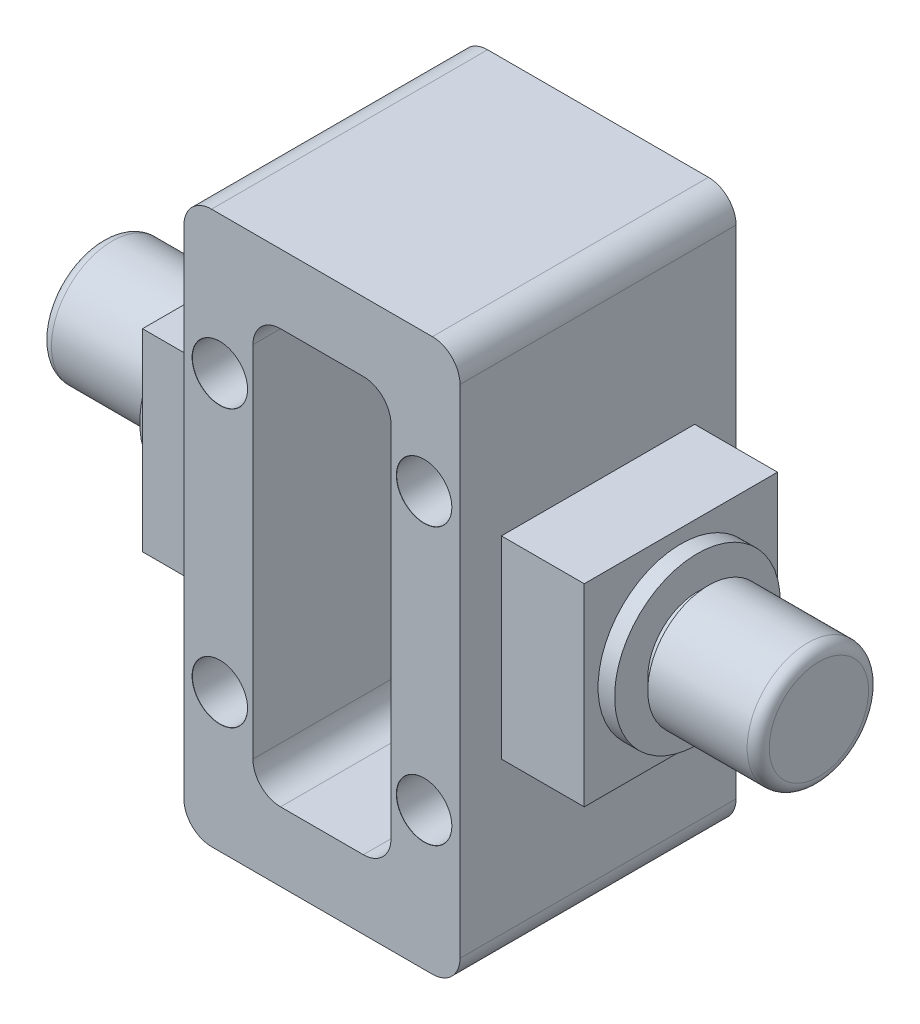
SolidWorks part; units mm, degrees
ref_plane "Front Plane" through (0, 0, 0) normal (0, 0, 1) x (1, 0, 0)
ref_plane "Top Plane" through (0, 0, 0) normal (0, 1, 0) x (1, 0, 0)
ref_plane "Right Plane" through (0, 0, 0) normal (1, 0, 0) x (0, 0, -1)
sketch "Sketch1" plane through (0, 0, 0) normal (1, 0, 0) x (0, 0, -1)
  line L1 (-25, 50) -> (25, 50)
  line L2 (-25, 50) -> (-25, -50)
  line L3 (-25, -50) -> (25, -50)
  line L4 (25, 50) -> (25, -50)
  line L5 (-25, 50) -> (25, -50) construction
  line L6 (-25, -50) -> (25, 50) construction
  point P0 (0, 0)
  dimension "D1" = 50
  dimension "D2" = 100
extrude "Boss-Extrude1" add sketch "Sketch1" along normal mid plane 50
fillet "Fillet1" radius 5 4 edges at (-25, 50, 0) (-25, -50, 0) (25, -50, 0) (25, 50, 0)
sketch "Sketch2" plane through (0, 0, 25) normal (0, 0, 1) x (1, 0, 0)
  line L8 (12.5, 37.5) -> (-12.5, 37.5)
  line L9 (-12.5, 37.5) -> (-12.5, -37.5)
  line L10 (-12.5, -37.5) -> (12.5, -37.5)
  line L11 (12.5, -37.5) -> (12.5, 37.5)
  line L12 (12.5, 37.5) -> (-12.5, 37.5)
  line L13 (-12.5, 37.5) -> (-12.5, -37.5)
  line L14 (-12.5, -37.5) -> (12.5, -37.5)
  line L15 (12.5, -37.5) -> (12.5, 37.5)
  dimension "D1" = 12.5
extrude "Cut-Extrude1" cut sketch "Sketch2" against normal blind 50
fillet "Fillet2" radius 5 4 edges at (12.5, -37.5, 0) (-12.5, -37.5, 0) (12.5, 37.5, 0) (-12.5, 37.5, 0)
sketch "Sketch4" plane through (-25, 0, 0) normal (-1, 0, 0) x (0, 0, 1)
  line L1 (-17.5, 17.5) -> (17.5, 17.5)
  line L2 (-17.5, 17.5) -> (-17.5, -17.5)
  line L3 (-17.5, -17.5) -> (17.5, -17.5)
  line L4 (17.5, 17.5) -> (17.5, -17.5)
  line L5 (-17.5, 17.5) -> (17.5, -17.5) construction
  line L6 (-17.5, -17.5) -> (17.5, 17.5) construction
  point P0 (0, 0)
  dimension "D1" = 35
  dimension "D2" = 35
extrude "Boss-Extrude2" add sketch "Sketch4" along normal blind 15
mirror "Mirror1" about plane through (0, 0, 0) normal (1, 0, 0) of "Boss-Extrude2"
sketch "Sketch6" plane through (0, 0, 0) normal (0, 0, 1) x (1, 0, 0)
  line L0 (0, 0) -> (-84.3212, 0) construction
  line L1 (-40, 15) -> (-43, 15)
  line L2 (-40, -17.5) -> (-40, 17.5) construction
  line L3 (-43, 15) -> (-43, 9)
  line L4 (-43, 9) -> (-45, 9)
  line L5 (-45, 9) -> (-45, 11)
  line L6 (-45, 11) -> (-65, 11)
  line L7 (-65, 11) -> (-65, 0)
  line L8 (-65, 0) -> (-40, 0)
  line L9 (-40, 0) -> (-40, 15)
  line L10 (-25, -17.5) -> (-25, 17.5) construction
  dimension "D1" = 20
  dimension "D2" = 3
  dimension "D3" = 40
  dimension "D4" = 15
  dimension "D5" = 11
  dimension "D6" = 9
revolve "Revolve1" add sketch "Sketch6" angle 360 about L0
mirror "Mirror2" about plane through (0, 0, 0) normal (1, 0, 0) of "Revolve1"
fillet "Fillet7" radius 2 1 edges at (-65, 0, -11)
fillet "Fillet8" radius 2 1 edges at (65, 0, -11)
hole_wizard "Ø10.0mm Dowel Hole1" positions "Sketch10" profile "Sketch12" hole size "Ø10.0" standard "ISO" end condition through all
sketch "Sketch10" plane through (0, 0, 25) normal (0, 0, 1) x (1, 0, 0)
  point P0 (18.5, 25)
  point P2 (18.5, -25)
  point P4 (-18.5, -25)
  point P6 (-18.5, 25)
  point P9 (0, 0)
  point P10 (0, 0)
  point P11 (0, 0)
  point P12 (0, 0)
  dimension "D1" = 37
  dimension "D2" = 50
  dimension "D3" = 25
  dimension "D4" = 18.5
sketch "Sketch12" plane through (18.5, 25, 25) normal (1, 0, 0) x (0, -1, 0)
  line L0 (0, 0) -> (0, 50)
  line L1 (0, 50) -> (5, 50)
  line L2 (5, 50) -> (5, 0.025)
  line L3 (5, 0.025) -> (5.025, 0)
  line L5 (5.025, 0) -> (0, 0)
  line L6 (-5, 0.025) -> (-5.025, 0) construction
  line L11 (0, -6.35) -> (0, 107.95) construction
  dimension "Thru Hole Dia." = 10
  dimension "Thru Hole Depth" = 50
  dimension "Near C'Sink Dia." = 10.05
  dimension "Near C'Sink Angle" = 90
